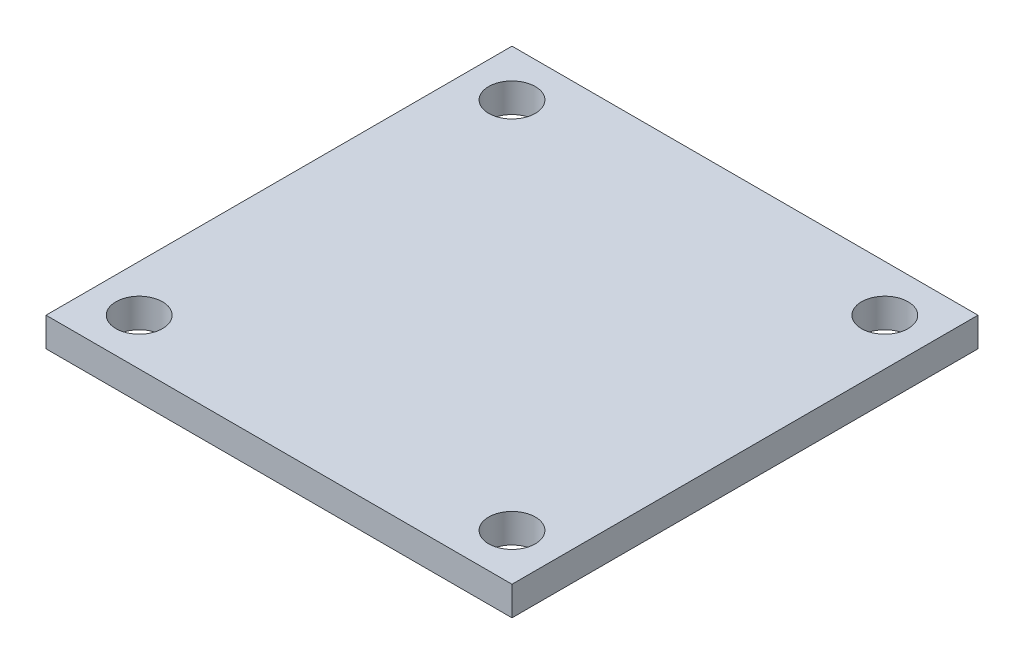
SolidWorks part; units mm, degrees
material "AISI 1045 Aço, trefilado"
ref_plane "Plano frontal" through (0, 0, 0) normal (0, 0, 1) x (1, 0, 0)
ref_plane "Plano superior" through (0, 0, 0) normal (0, 1, 0) x (1, 0, 0)
ref_plane "Plano direito" through (0, 0, 0) normal (1, 0, 0) x (0, 0, -1)
sketch "Esboço1" plane through (0, 0, 0) normal (0, 1, 0) x (1, 0, 0)
  line L1 (-100, 100) -> (100, 100)
  line L2 (-100, 100) -> (-100, -100)
  line L3 (-100, -100) -> (100, -100)
  line L4 (100, 100) -> (100, -100)
  line L5 (-100, 100) -> (100, -100) construction
  line L6 (-100, -100) -> (100, 100) construction
  point P0 (0, 0)
  dimension "D1" = 200
  dimension "D2" = 200
extrude "Ressalto-extrusão1" add sketch "Esboço1" along normal blind 12.5
sketch "Esboço2" plane through (0, 12.5, 0) normal (0, 1, 0) x (1, 0, 0)
  line L0 (100, 100) -> (-100, 100) construction
  line L1 (-100, 100) -> (-100, -100) construction
  circle A0 centre (-80, 80) radius 10
  dimension "D1" = 20
  dimension "D2" = 20
  dimension "D3" = 20
extrude "Corte-extrusão1" cut sketch "Esboço2" against normal through all
pattern_linear "Padrão linear1" count 2 spacing 160 along (1, 0, 0) count 2 spacing 160 along (0, 0, 1) of "Corte-extrusão1"
